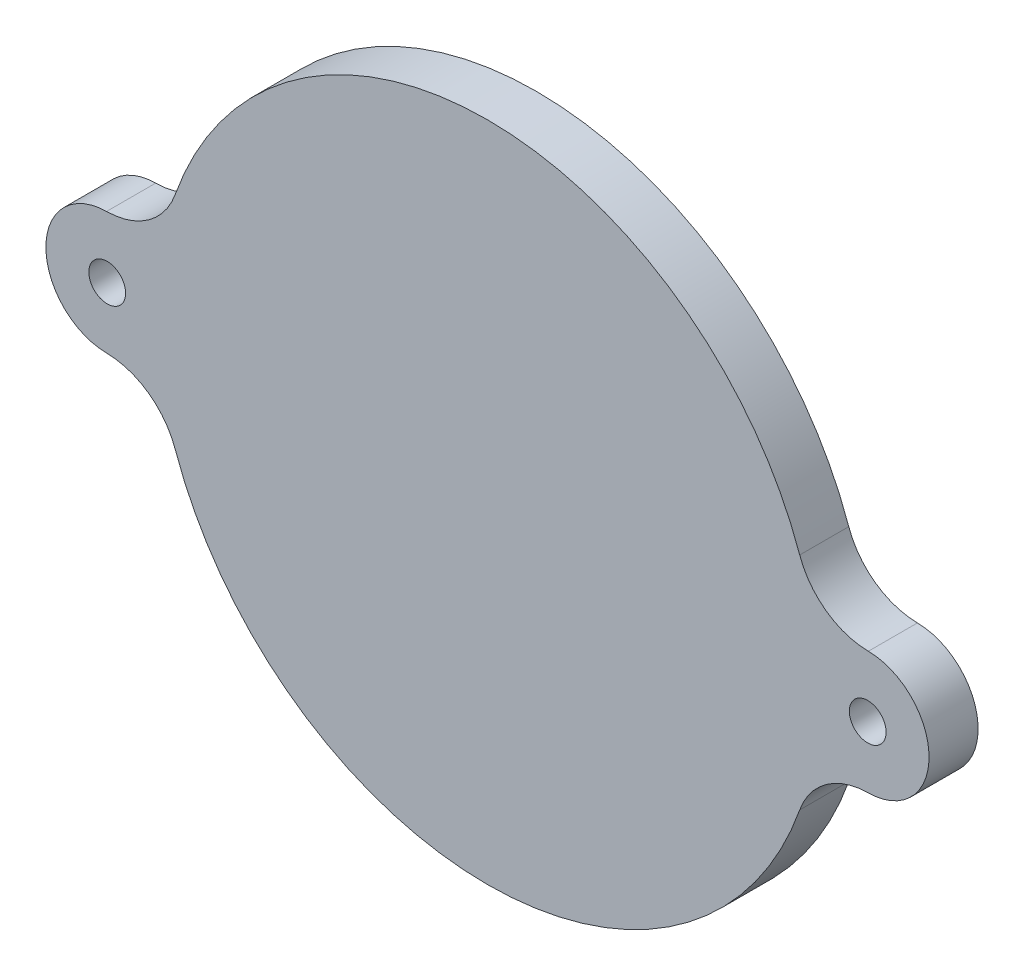
SolidWorks part; units mm, degrees
material "合金钢"
ref_plane "前视基准面" through (0, 0, 0) normal (0, 0, 1) x (1, 0, 0)
ref_plane "上视基准面" through (0, 0, 0) normal (0, 1, 0) x (1, 0, 0)
ref_plane "右视基准面" through (0, 0, 0) normal (1, 0, 0) x (0, 0, -1)
sketch "草图1" plane through (0, 0, 0) normal (0, 0, 1) x (1, 0, 0)
  line L0 (0, 0) -> (27, 0) construction
  line L1 (27, 0) -> (31, 0) construction
  line L2 (0, 0) -> (-27, 0) construction
  line L3 (-27, 0) -> (-31, 0) construction
  arc A1 (-26.8548, -2.796) -> (26.8548, -2.796) centre (0, 0) ccw
  circle A2 centre (31, 0) radius 1.5
  circle A3 centre (-31, 0) radius 1.5
  arc A4 (26.8548, -2.796) -> (26.8548, 2.796) centre (31, 0) ccw
  arc A6 (-26.8548, 2.796) -> (-26.8548, -2.796) centre (-31, 0) ccw
  arc A7 (26.8548, 2.796) -> (-26.8548, 2.796) centre (0, 0) ccw
extrude "凸台-拉伸3" add sketch "草图1" along normal blind 4
fillet "圆角1" radius 6 4 edges at (-26.8548, 2.796, 2) (-26.8548, -2.796, 2) (26.8548, -2.796, 2) (26.8548, 2.796, 2)
